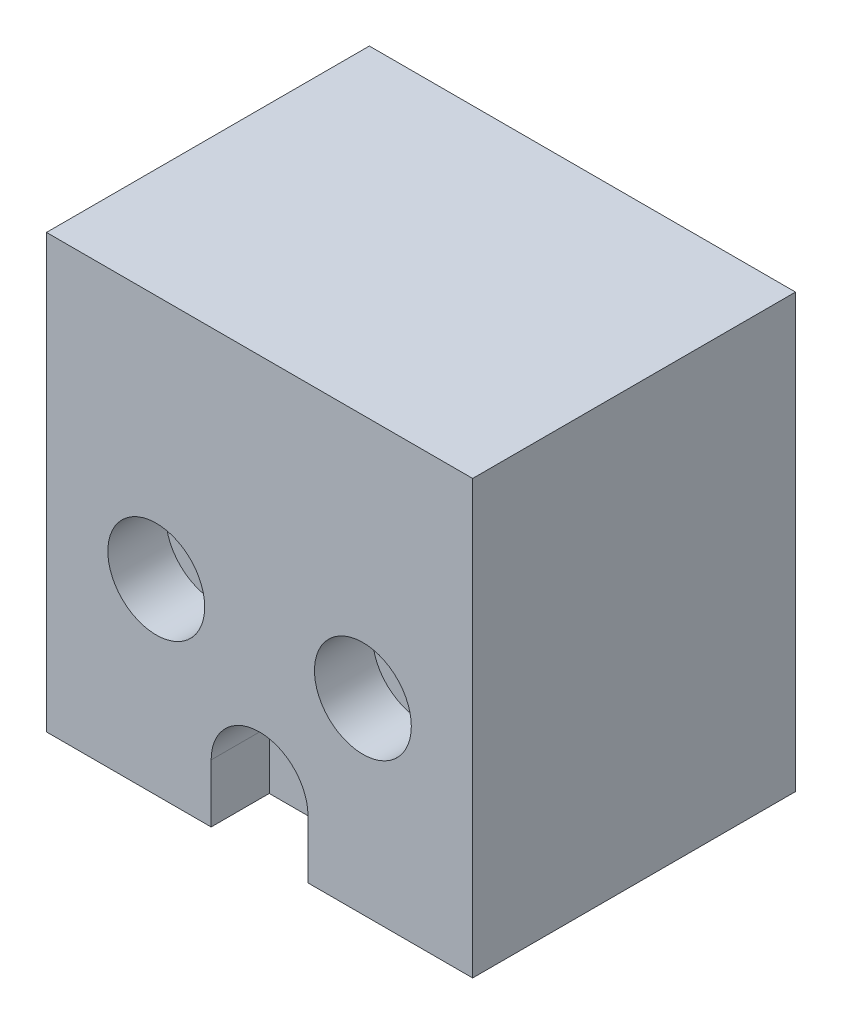
SolidWorks part; units mm, degrees
material "6061-O (SS)"
ref_plane "Front" through (0, 0, 0) normal (0, 0, 1) x (1, 0, 0)
ref_plane "Top" through (0, 0, 0) normal (0, 1, 0) x (1, 0, 0)
ref_plane "Right" through (0, 0, 0) normal (1, 0, 0) x (0, 0, -1)
sketch "Base_Sketch" plane through (0, 0, 0) normal (0, 0, 1) x (1, 0, 0)
  line L1 (-16.5, 33.5) -> (16.5, 33.5)
  line L2 (-16.5, 33.5) -> (-16.5, 0)
  line L3 (-16.5, 0) -> (16.5, 0)
  line L4 (16.5, 33.5) -> (16.5, 0)
  dimension "Width" = 33
  dimension "Height" = 33.5
extrude "Base" add sketch "Base_Sketch" against normal blind 25
sketch "Drill_Sketch" plane through (0, 0, 0) normal (0, 0, 1) x (1, 0, 0)
  line L0 (0, 0) -> (0, 17.6516) construction
  line L1 (-16.5, 0) -> (16.5, 0) construction
  circle A0 centre (0, 4.5) radius 2.25
  circle A1 centre (-8, 14.5) radius 2.25
  circle A2 centre (8, 14.5) radius 2.25
  dimension "Diameter" = 4.5
  dimension "Height1" = 4.5
  dimension "Height2" = 14.5
  dimension "Space" = 16
extrude "Drill" cut sketch "Drill_Sketch" against normal through all
ref_plane "Depth" through (0, 0, -4.5) normal (0, 0, 1) x (1, 0, 0)
sketch "Mill_Sketch" plane through (0, 0, 0) normal (0, 0, 1) x (1, 0, 0)
  line L0 (-3.75, 0) -> (-3.75, 4.5)
  line L1 (-16.5, 0) -> (16.5, 0) construction
  line L2 (-3.75, 4.5) -> (3.75, 4.5)
  line L3 (3.75, 4.5) -> (3.75, 0)
  line L4 (3.75, 0) -> (-3.75, 0)
  dimension "Width" = 7.5
extrude "Mill" cut sketch "Mill_Sketch" against normal up to surface (4.5 mm away)
sketch "C_Bore_Sketch" plane through (0, 0, 0) normal (0, 0, 1) x (1, 0, 0)
  circle A0 centre (-8, 14.5) radius 3.75
  circle A1 centre (8, 14.5) radius 3.75
  circle A2 centre (0, 4.5) radius 3.75
  dimension "Diameter" = 7.5
extrude "C_Bore" cut sketch "C_Bore_Sketch" against normal up to surface (4.5 mm away)
